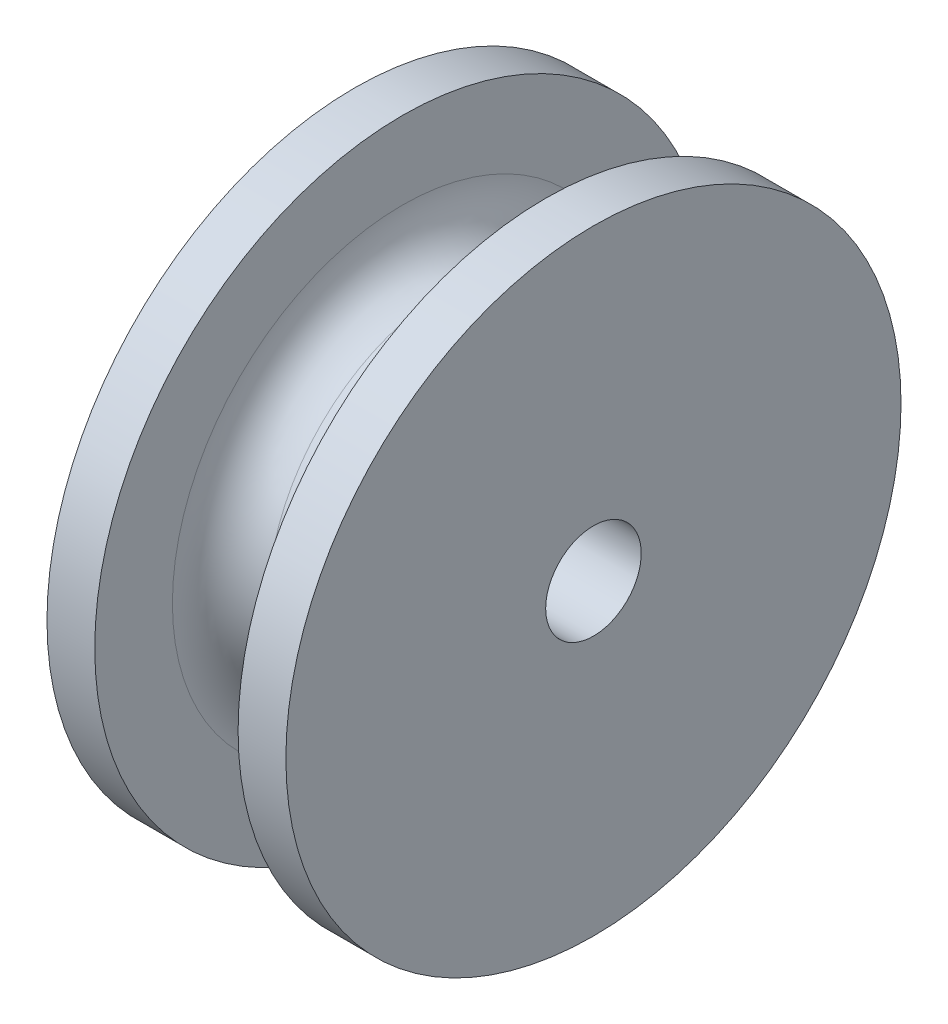
SolidWorks part; units mm, degrees
ref_plane "Front Plane" through (0, 0, 0) normal (1, 0, 0) x (0, 1, 0)
ref_plane "Top Plane" through (0, 0, 0) normal (0, 0, 1) x (0, 1, 0)
ref_plane "Right Plane" through (0, 0, 0) normal (0, 1, 0) x (-1, 0, 0)
sketch "Sketch1" plane through (0, 0, 0) normal (0, 1, 0) x (-1, 0, 0)
  line L1 (-10, 0) -> (-10, 25.75)
  line L2 (-10, 25.75) -> (-6, 25.75)
  line L3 (-6, 25.75) -> (-6, 15.25)
  line L4 (-6, 15.25) -> (6, 15.25)
  line L5 (0, 15.25) -> (0, 0) construction
  line L6 (6, 25.75) -> (6, 15.25)
  line L7 (10, 25.75) -> (6, 25.75)
  line L8 (10, 0) -> (10, 25.75)
  line L9 (-10, 0) -> (10, 0)
  dimension "D1" = 25.75
  dimension "D2" = 20
  dimension "D3" = 4
  dimension "D4" = 10.5
revolve "Revolve1" add sketch "Sketch1" angle 360 about L9
fillet "Fillet1" radius 4 2 edges at (-6, 0, -15.25) (6, 0, -15.25)
sketch "Sketch3" plane through (-10, 0, 0) normal (-1, 0, 0) x (0, -1, 0)
  circle A0 centre (0, 0) radius 4
  dimension "D1" = 8
extrude "Cut-Extrude1" cut sketch "Sketch3" against normal through all
